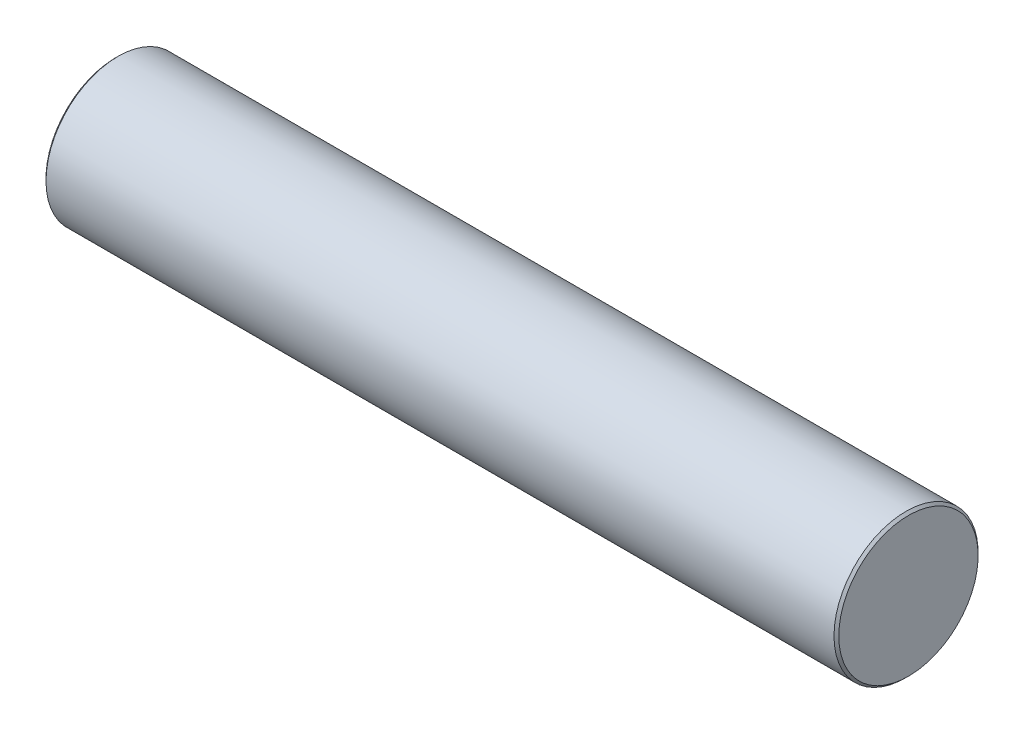
SolidWorks part; units mm, degrees
material "45"
ref_plane "前视基准面" through (0, 0, 0) normal (0, 0, 1) x (1, 0, 0)
ref_plane "上视基准面" through (0, 0, 0) normal (0, 1, 0) x (1, 0, 0)
ref_plane "右视基准面" through (0, 0, 0) normal (1, 0, 0) x (0, 0, -1)
sketch "草图1" plane through (0, 0, 0) normal (1, 0, 0) x (0, -1, 0)
  circle A0 centre (0, 0) radius 30
  dimension "D1" = 60
extrude "凸台-拉伸1" add sketch "草图1" along normal mid plane 330
chamfer "倒角1" distance 1 angle 45 2 edges at (-165, 0, -30) (165, 0, -30)
hole_wizard "M12 螺纹孔1" [suppressed] positions "3D草图1" profile "草图2" tap size "M12" standard "GB"
sketch3d "3D草图1"
  line L0 (0, -164, 0) -> (0, -165, 0) construction
  point P0 (0, -165, 0)
cosmetic thread "孔螺蚊线1" [suppressed] parameters "D1"=24, "D2"=12
sketch "草图2" plane through (0, -165, 0) normal (1, 0, 0) x (0, 0, -1)
  line L0 (0, 0) -> (0, 35.8144)
  line L1 (0, 35.8144) -> (5.1, 32.75)
  line L2 (5.1, 32.75) -> (5.1, 0)
  line L5 (5.1, 0) -> (0, 0)
  line L10 (0, 35.8144) -> (-5.1, 32.75) construction
  line L11 (0, -6.35) -> (0, 107.95) construction
  dimension "螺纹孔钻头直径" = 10.2
  dimension "螺纹孔钻头深度" = 32.75
  dimension "导头角度" = 118
